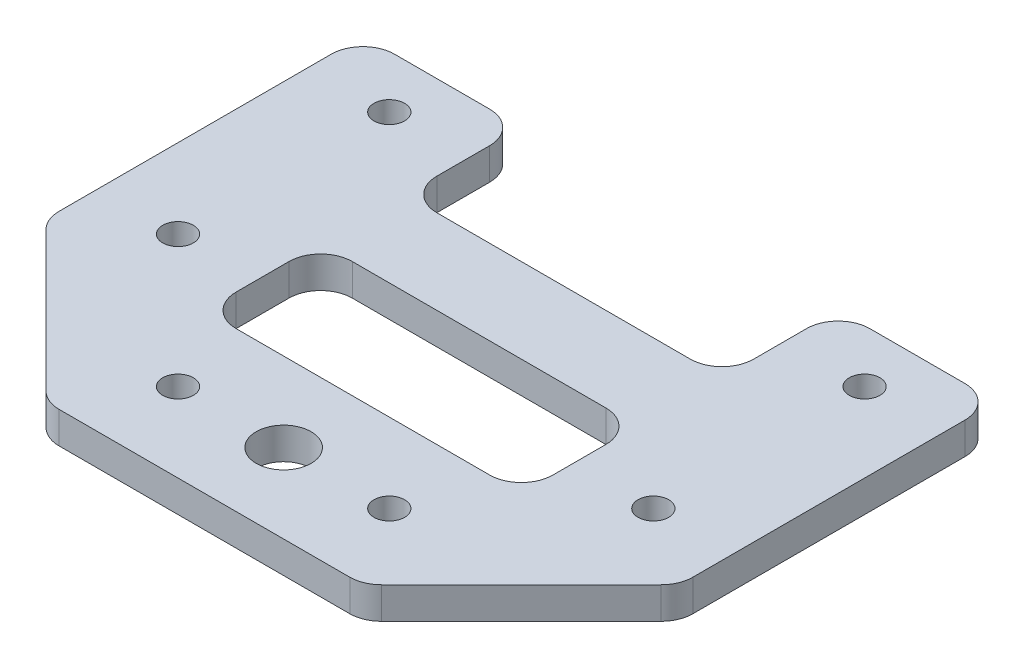
SolidWorks part; units mm, degrees
material "Thornel Mat VMA"
ref_plane "前视基准面" through (0, 0, 0) normal (0, 0, 1) x (1, 0, 0)
ref_plane "上视基准面" through (0, 0, 0) normal (0, 1, 0) x (1, 0, 0)
ref_plane "右视基准面" through (0, 0, 0) normal (1, 0, 0) x (0, 0, -1)
other "Configuration Table"
sketch "草图1" plane through (0, 0, 0) normal (0, 1, 0) x (1, 0, 0)
  line L1 (-15, -10) -> (15, -10)
  line L2 (-15, -10) -> (-15, 10)
  line L3 (-15, 10) -> (15, 10)
  line L4 (15, -10) -> (15, 10)
  line L5 (-15, -10) -> (15, 10) construction
  line L6 (-15, 10) -> (15, -10) construction
  point P0 (0, 0)
  dimension "D1" = 20
  dimension "D2" = 30
extrude "凸台-拉伸1" add sketch "草图1" along normal blind 3
sketch "草图2" plane through (0, 3, 0) normal (0, 1, 0) x (1, 0, 0)
  line L1 (-5, -7.5) -> (5, -7.5) construction
  line L2 (-5, -7.5) -> (-5, 7.5) construction
  line L3 (-5, 7.5) -> (5, 7.5) construction
  line L4 (5, -7.5) -> (5, 7.5) construction
  line L5 (-5, -7.5) -> (5, 7.5) construction
  line L6 (-5, 7.5) -> (5, -7.5) construction
  circle A0 centre (-5, 7.5) radius 1.6
  circle A1 centre (5, 7.5) radius 1.6
  circle A2 centre (5, -7.5) radius 1.6
  circle A3 centre (-5, -7.5) radius 1.6
  point P0 (0, 0)
  dimension "D3" = 3.2
  dimension "D4" = 3.2
  dimension "D5" = 3.2
  dimension "D6" = 3.2
  dimension "D1" = 15
  dimension "D2" = 10
extrude "切除-拉伸1" cut sketch "草图2" against normal through all
sketch "草图3" plane through (0, 3, 0) normal (0, 1, 0) x (1, 0, 0)
  line L0 (-22.5, 15) -> (-22.5, -15) construction
  line L1 (15, 15) -> (30, 15)
  line L2 (15, 15) -> (15, -15)
  line L3 (15, -15) -> (30, -15)
  line L4 (30, 15) -> (30, -15)
  line L5 (-15, 15) -> (-30, 15)
  line L6 (-15, 15) -> (-15, -15)
  line L7 (-15, -15) -> (-30, -15)
  line L8 (-30, 15) -> (-30, -15)
  line L9 (22.5, 15) -> (22.5, -15) construction
  line L10 (0, 0) -> (0, -10) construction
  line L11 (-15, -10) -> (15, -10) construction
  line L12 (-30, 0) -> (-15, 0) construction
  line L13 (-15, 10) -> (-15, -10) construction
  line L14 (15, -10) -> (15, 10) construction
  line L15 (30, 0) -> (15, 0) construction
  circle A0 centre (-22.5, 10) radius 1.45
  circle A1 centre (-22.5, -10) radius 1.45
  circle A2 centre (22.5, -10) radius 1.45
  circle A3 centre (22.5, 10) radius 1.45
  dimension "D5" = 2.9
  dimension "D6" = 2.9
  dimension "D7" = 5
  dimension "D8" = 5
  dimension "D1" = 30
  dimension "D2" = 15
  dimension "D3" = 30
  dimension "D4" = 15
extrude "凸台-拉伸2" add sketch "草图3" against normal blind 3
sketch "草图4" plane through (0, 0, 0) normal (0, -1, 0) x (1, 0, 0)
  line L0 (15, 10) -> (15, 15) construction
  line L1 (-15, 10) -> (15, 10)
  line L2 (-15, 10) -> (-15, 4)
  line L3 (-15, 4) -> (15, 4)
  line L4 (15, 10) -> (15, 4)
  line L5 (0, 0) -> (30, 0) construction
  line L6 (30, 15) -> (30, -15) construction
  line L7 (15, -10) -> (15, -4)
  line L8 (-15, -4) -> (15, -4)
  line L9 (-15, -10) -> (-15, -4)
  line L10 (-15, -10) -> (15, -10)
  dimension "D1" = 6
extrude "切除-拉伸2" cut sketch "草图4" against normal through all
sketch "草图5" plane through (0, 3, 0) normal (0, 1, 0) x (1, 0, 0)
  line L0 (30, -15) -> (30, 15) construction
  line L5 (15, -15) -> (30, -15)
  line L9 (-30, -15) -> (30, -15)
  line L10 (-30, -15) -> (-30, -30)
  line L11 (-30, -30) -> (30, -30)
  line L12 (30, -15) -> (30, -30)
  line L13 (-30, -22.5) -> (30, -22.5) construction
  line L14 (0, 0) -> (0, -22.5) construction
  circle A3 centre (-10, -22.5) radius 1.45
  circle A4 centre (10, -22.5) radius 1.45
  circle A5 centre (0, -22.5) radius 2.6
  line M5 (15, -15) -> (30, -15)
  line M13 (-30, -15) -> (-15, -15)
  dimension "D3" = 2.9
  dimension "D4" = 10
  dimension "D2" = 2.9
  dimension "D6" = 5.2
  dimension "D1" = 15
  dimension "D5" = 10
extrude "凸台-拉伸3" add sketch "草图5" against normal blind 3 contours L12 L9 L10 L11 A5 A4 A3 M5 M13
sketch "草图6" plane through (0, 3, 0) normal (0, 1, 0) x (1, 0, 0)
  line L0 (-30, -15) -> (-15, -30)
  line L1 (-30, 15) -> (-30, -30) construction
  line L2 (-30, -30) -> (30, -30) construction
  line L3 (-15, -30) -> (-30, -30)
  line L4 (-30, -30) -> (-30, -15)
  line L5 (-15, -15) -> (-15, -4) construction
  line L6 (-15, -15) -> (15, -15) construction
  line L7 (0, 0) -> (0, -30) construction
  line L8 (30, -30) -> (30, -15)
  line L9 (15, -30) -> (30, -30)
  line L10 (30, -15) -> (15, -30)
extrude "切除-拉伸3" cut sketch "草图6" against normal through all
fillet "圆角1" radius 3 14 edges at (15, 1.5, -4) (15, 1.5, -15) (15, 1.5, 4) (15, 1.5, 15) (-15, 1.5, 4) (-15, 1.5, 15) (-15, 1.5, -4) (-15, 1.5, -15) (-15, 1.5, 30) (15, 1.5, 30) (30, 1.5, 15) (30, 1.5, -15) (-30, 1.5, -15) (-30, 1.5, 15)
